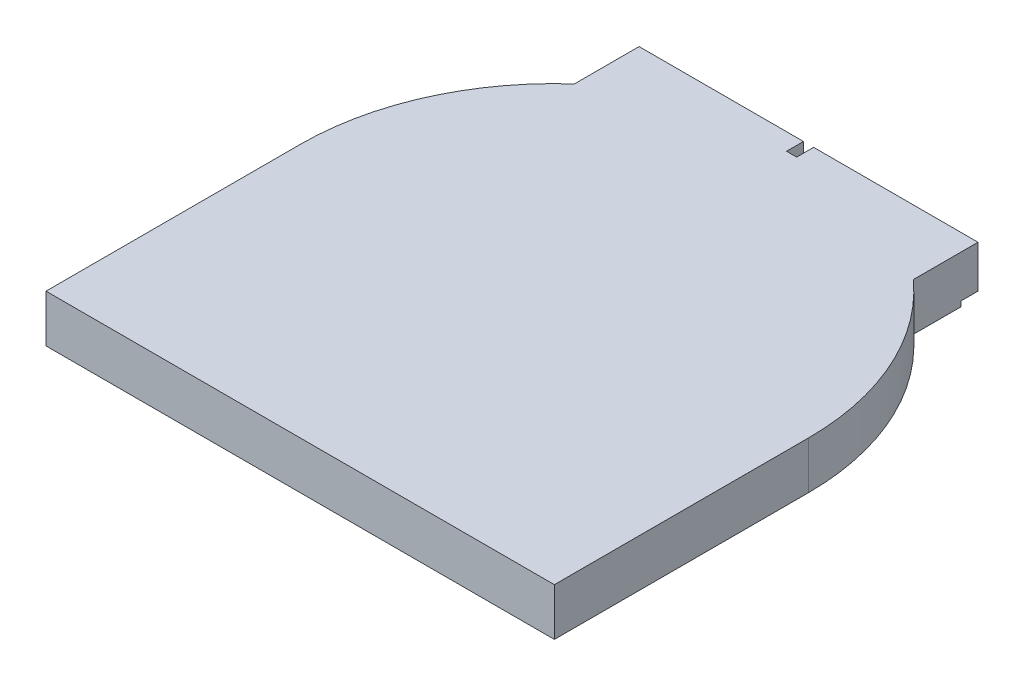
SolidWorks part; units mm, degrees
ref_plane "Front Plane" through (0, 0, 0) normal (0, 0, 1) x (1, 0, 0)
ref_plane "Top Plane" through (0, 0, 0) normal (0, 1, 0) x (1, 0, 0)
ref_plane "Right Plane" through (0, 0, 0) normal (1, 0, 0) x (0, 0, -1)
sketch "Sketch1" plane through (0, 0, 0) normal (0, 1, 0) x (1, 0, 0)
  line L0 (-5, 7.5) -> (-5, 5.5902)
  line L2 (-3, 5.5) -> (-3, 5.1235)
  line L4 (3, 5.5) -> (3, 5.1235)
  line L5 (5, 7.5) -> (5, 5.5902)
  line L6 (-5, 7.5) -> (-3, 7.5)
  line L7 (-3, 5.5) -> (-3, 7.5)
  line L8 (3, 5.5) -> (3, 7.5)
  line L9 (3, 7.5) -> (5, 7.5)
  line L10 (-5, 7.5) -> (5, 7.5) construction
  line L11 (-3, 5.5) -> (3, 5.5) construction
  line L12 (-7.5, 0) -> (-7.5, -7.5)
  line L13 (-7.5, -7.5) -> (7.5, -7.5)
  line L14 (7.5, -7.5) -> (7.5, 0)
  arc A0 (-3.3846, 4.3352) -> (3.3846, 4.3352) centre (0, 0) ccw
  arc A1 (-3.3846, 4.3352) -> (-3, 5.1235) centre (-4, 5.1235) ccw
  arc A2 (3.3846, 4.3352) -> (3, 5.1235) centre (4, 5.1235) cw
  arc A3 (-5, 5.5902) -> (-5, 5.5902) centre (-5, 5.5902) ccw
  arc A4 (-5, 5.5902) -> (-7.5, 0) centre (0, 0) ccw
  arc A5 (5, 5.5902) -> (5, 5.5902) centre (5, 5.5902) cw
  arc A6 (7.5, 0) -> (5, 5.5902) centre (0, 0) ccw
  arc A7 (-5, 5.5902) -> (5, 5.5902) centre (0, 0) ccw construction
  point P19 (-7.5, 0)
  point P22 (7.5, 0)
  point P23 (0, -7.5)
  dimension "D1" = 11
  dimension "D4" = 1
  dimension "D6" = 1
  dimension "D2" = 6
  dimension "D3" = 3
  dimension "D5" = 7.5
  dimension "D7" = 2
extrude "Boss-Extrude1" add sketch "Sketch1" along normal blind 0.8
sketch "Sketch2" plane through (0, 0.8, 0) normal (0, 1, 0) x (1, 0, 0)
  line L0 (5, 5.5902) -> (5, 7.5) construction
  line L1 (5, 7.5) -> (3, 7.5) construction
  line L2 (-5, 7.5) -> (-5, 5.5902) construction
  line L3 (-3, 7.5) -> (-5, 7.5) construction
  line L4 (5, 5.5902) -> (5, 7.5)
  line L5 (5, 7.5) -> (3, 7.5)
  line L6 (-5, 7.5) -> (-5, 5.5902)
  line L7 (-3, 7.5) -> (-5, 7.5)
  line L8 (-3, 7.5) -> (3, 7.5)
  line L9 (7.5, -7.5) -> (7.5, 0) construction
  line L10 (-7.5, -7.5) -> (7.5, -7.5) construction
  line L11 (-7.5, 0) -> (-7.5, -7.5) construction
  line L12 (7.5, -7.5) -> (7.5, 0)
  line L13 (-7.5, -7.5) -> (7.5, -7.5)
  line L14 (-7.5, 0) -> (-7.5, -7.5)
  arc A2 (7.5, 0) -> (5, 5.5902) centre (0, 0) ccw construction
  arc A3 (-5, 5.5902) -> (-7.5, 0) centre (0, 0) ccw construction
  arc A4 (7.5, 0) -> (5, 5.5902) centre (0, 0) ccw
  arc A5 (-5, 5.5902) -> (-7.5, 0) centre (0, 0) ccw
extrude "Boss-Extrude2" add sketch "Sketch2" along normal blind 1
sketch "Sketch3" plane through (0, 0, 0) normal (0, -1, 0) x (1, 0, 0)
  line L0 (-3, -7.5) -> (-5, -7.5) construction
  line L1 (5, -7.5) -> (3, -7.5) construction
  line L2 (5, -5.5902) -> (5, -7.5) construction
  line L3 (-5, -7.5) -> (-5, -5.5902) construction
  line L4 (-3, -7.5) -> (-5, -7.5)
  line L5 (5, -7.5) -> (3, -7.5)
  line L6 (5, -5.5902) -> (5, -7.5)
  line L7 (-5, -7.5) -> (-5, -5.5902)
  line L8 (-3, -7.5) -> (3, -7.5)
  line L9 (-7.5, 0) -> (-7.5, 7.5) construction
  line L10 (-7.5, 7.5) -> (7.5, 7.5) construction
  line L11 (7.5, 7.5) -> (7.5, 0) construction
  line L12 (-7.5, 0) -> (-7.5, 7.5)
  line L13 (-7.5, 7.5) -> (7.5, 7.5)
  line L14 (7.5, 7.5) -> (7.5, 0)
  arc A2 (-7.5, 0) -> (-5, -5.5902) centre (0, 0) ccw construction
  arc A3 (5, -5.5902) -> (7.5, 0) centre (0, 0) ccw construction
  arc A4 (-7.5, 0) -> (-5, -5.5902) centre (0, 0) ccw
  arc A5 (5, -5.5902) -> (7.5, 0) centre (0, 0) ccw
extrude "Boss-Extrude3" add sketch "Sketch3" along normal blind 1
sketch "Sketch4" plane through (0, 0, -7.5) normal (0, 0, -1) x (-1, 0, 0)
  line L0 (-5, 1.8) -> (-5, -1) construction
  line L3 (-5, 1.8) -> (-5, -1) construction
  line L4 (-5, 0.55) -> (-0.15, 0.55)
  line L5 (-5, 0.55) -> (-5, 0.25)
  line L6 (-5, 0.25) -> (-0.15, 0.25)
  line L7 (5, 0.55) -> (5, 0.25)
  line L8 (5, 1.8) -> (5, -1) construction
  line L9 (-3, 0.8) -> (3, 0.8) construction
  line L10 (-5, 1.8) -> (5, 1.8) construction
  line L11 (-0.15, 1.8) -> (0.15, 1.8)
  line L12 (-0.15, 1.8) -> (-0.15, 0.55)
  line L13 (-0.15, -1) -> (0.15, -1)
  line L14 (0.15, 1.8) -> (0.15, 0.55)
  line L15 (5, -1) -> (-5, -1) construction
  line L16 (0.15, 0.55) -> (5, 0.55)
  line L17 (0.15, 0.25) -> (5, 0.25)
  line L18 (0.15, 0.25) -> (0.15, -1)
  line L19 (-0.15, 0.25) -> (-0.15, -1)
  point P0 (-5, 0.4)
  point P1 (0, 0.8)
  dimension "D1" = 0.3
  dimension "D2" = 0.15
  dimension "D3" = 0.3
  dimension "D4" = 0.15
extrude "Cut-Extrude1" cut sketch "Sketch4" against normal blind 0.5
ref_plane "Plane1" through (0, 0.4, 0) normal (0, -1, 0) x (-1, 0, 0)
sketch "Sketch5" plane through (0, 0.4, 0) normal (0, -1, 0) x (-1, 0, 0)
  line L1 (-9.1662, 8.5407) -> (9.8031, 8.5407)
  line L2 (-9.1662, 8.5407) -> (-9.1662, -8.4498)
  line L3 (-9.1662, -8.4498) -> (9.8031, -8.4498)
  line L4 (9.8031, 8.5407) -> (9.8031, -8.4498)
extrude "Cut-Extrude2" cut sketch "Sketch5" along normal blind 4
